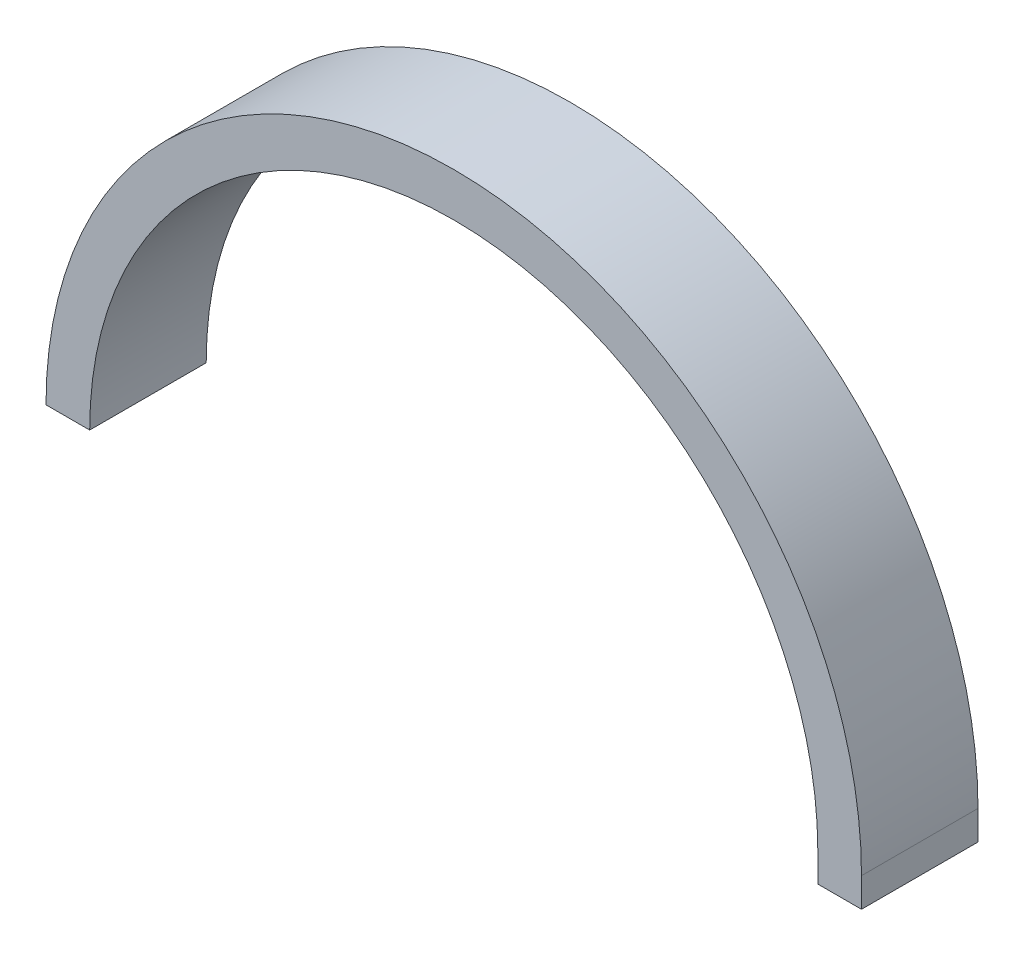
SolidWorks part; units mm, degrees
ref_plane "前视基准面" through (0, 0, 0) normal (0, 0, 1) x (1, 0, 0)
ref_plane "上视基准面" through (0, 0, 0) normal (0, 1, 0) x (1, 0, 0)
ref_plane "右视基准面" through (0, 0, 0) normal (1, 0, 0) x (0, 0, -1)
other "Configuration Table"
sketch "草图1" plane through (0, 0, 0) normal (0, 0, 1) x (1, 0, 0)
  line L0 (-125, 0) -> (125, 0) construction
  line L1 (-125, 0) -> (-140, 0)
  line L2 (125, 0) -> (140, 0)
  circle A0 centre (0, 0) radius 125 construction
  arc A1 (-125, 0) -> (125, 0) centre (0, 0) cw
  arc A2 (-140, 0) -> (140, 0) centre (0, 0) cw
  dimension "D1" = 250
  dimension "D2" = 140
extrude "凸台-拉伸1" add sketch "草图1" along normal blind 40
sketch "草图3" plane through (0, 0, 0) normal (0, -1, 0) x (1, 0, 0)
  line L1 (125, 40) -> (140, 40)
  line L2 (125, 40) -> (125, 0)
  line L3 (125, 0) -> (140, 0)
  line L4 (140, 40) -> (140, 0)
extrude "凸台-拉伸3" add sketch "草图3" along normal blind 10
